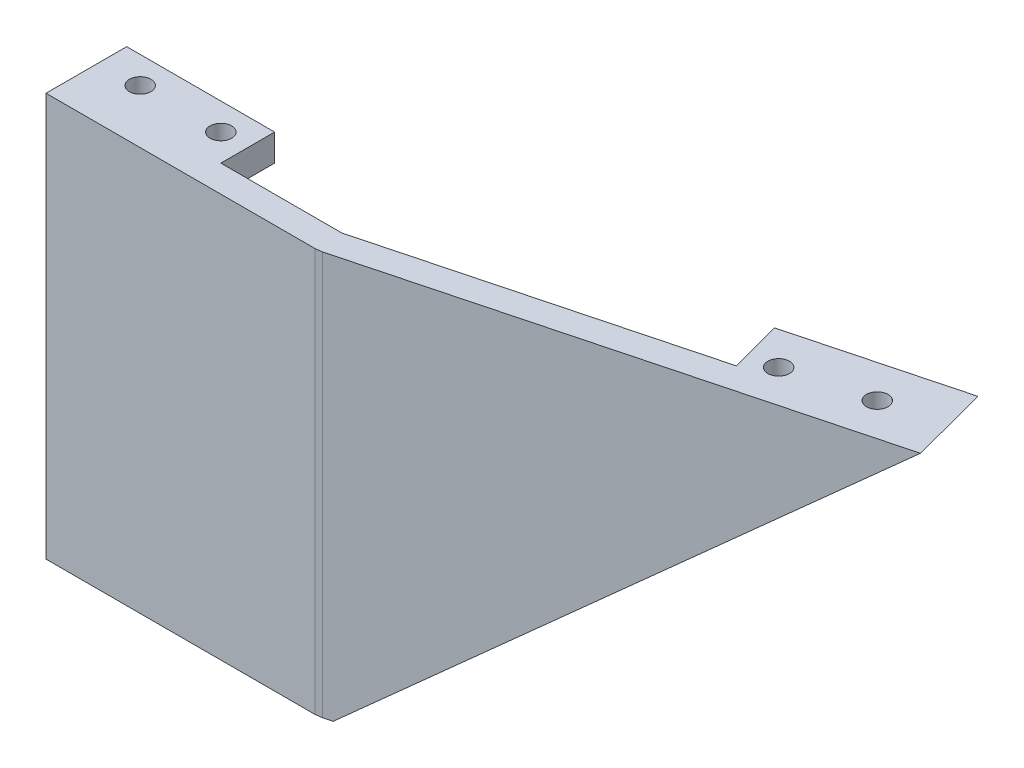
SolidWorks part; units mm, degrees
ref_plane "前视基准面" through (0, 0, 0) normal (0, 0, 1) x (1, 0, 0)
ref_plane "上视基准面" through (0, 0, 0) normal (0, 1, 0) x (1, 0, 0)
ref_plane "右视基准面" through (0, 0, 0) normal (1, 0, 0) x (0, 0, -1)
sketch "草图1" plane through (0, 0, 0) normal (0, 0, 1) x (1, 0, 0)
  line L1 (-25, 75) -> (25, 75)
  line L2 (-25, 75) -> (-25, -75)
  line L3 (-25, -75) -> (25, -75)
  line L4 (25, 75) -> (25, -75)
  line L5 (0, -75) -> (0, 75) construction
  line L6 (-25, 0) -> (25, 0) construction
  point P0 (0, 0)
  dimension "D1" = 50
  dimension "D2" = 150
extrude "凸台-拉伸1" add sketch "草图1" along normal blind 10
sketch "草图2" plane through (0, 75, 0) normal (0, 1, 0) x (1, 0, 0)
  line L0 (-13, -10) -> (25, 0)
  line L2 (25, -10) -> (-25, -10) construction
  line L3 (-25, -10) -> (-25, 0) construction
  dimension "D1" = 12
ref_plane "基准面1" through (25, 75, 0) normal (0.9671, 0, -0.2545) x (-0.2545, 0, -0.9671)
sketch "草图3" plane through (25, 75, 0) normal (0.9671, 0, -0.2545) x (-0.2545, 0, -0.9671)
  line L1 (0, 0) -> (-10, 0)
  line L2 (0, 0) -> (0, -150)
  line L3 (0, -150) -> (-10, -150)
  line L4 (-10, 0) -> (-10, -150)
  dimension "D1" = 10
extrude "凸台-拉伸2" add sketch "草图3" along normal blind 280 separate body
sketch "草图4" plane through (25, 0, 0) normal (1, 0, 0) x (0, 0, -1)
  line L1 (-10, 75) -> (0, 75)
  line L2 (-10, 75) -> (-10, -75)
  line L3 (-10, -75) -> (0, -75)
  line L4 (0, 75) -> (0, -75)
sketch "草图5" plane through (23.3808, 0, -6.1528) normal (-0.9671, 0, 0.2545) x (0.2545, 0, 0.9671)
  line L1 (6.3623, 75) -> (16.3623, 75)
  line L2 (6.3623, 75) -> (6.3623, -75)
  line L3 (6.3623, -75) -> (16.3623, -75)
  line L4 (16.3623, 75) -> (16.3623, -75)
loft "放样8" add profiles "草图4", "草图5"
sketch "草图6" plane through (0, 75, 0) normal (0, 1, 0) x (1, 0, 0)
  line L0 (25, 0) -> (295.7809, 71.2581)
  line L1 (-25, 0) -> (25, 0)
  line L2 (-25, 0) -> (-25, 20)
  line L3 (-25, 20) -> (22.4125, 20)
  line L6 (295.7809, 71.2581) -> (290.691, 90.5996)
  line L7 (22.4125, 20) -> (290.691, 90.5996)
  dimension "D1" = 20
  dimension "D2" = 20
extrude "凸台-拉伸3" add sketch "草图6" against normal blind 10
sketch "草图7" plane through (1.6192, 0, 6.1528) normal (-0.2545, 0, -0.9671) x (-0.9671, 0, 0.2545)
  line L0 (-194.1769, 65) -> (-24.1769, -77.6469)
  line L1 (-304.1769, 65) -> (-26.7644, 65) construction
  line L2 (-24.1769, -75) -> (-24.1769, 65) construction
  line L3 (-24.1769, -77.6469) -> (26.7218, -75)
  line L4 (26.7218, -75) -> (44.2616, -115.4721)
  line L5 (44.2616, -115.4721) -> (-316.3235, -105.2869)
  line L6 (-316.3235, -105.2869) -> (-321.0351, 79.2961)
  line L7 (-321.0351, 79.2961) -> (-302.3028, 102.6817)
  line L8 (-302.3028, 102.6817) -> (-235.3154, 89.4169)
  line L9 (-194.1769, 65) -> (-227.1481, 92.6661)
  line L10 (-227.1481, 92.6661) -> (-235.3154, 89.4169)
  dimension "D1" = 40
  dimension "D2" = 110
extrude "切除-拉伸1" cut sketch "草图7" against normal mid plane 100
sketch "草图8" plane through (-25, 0, 0) normal (-1, 0, 0) x (0, 0, 1)
  line L6 (0, 65) -> (0, -75)
  line L7 (0, -75) -> (10, -75)
  line L8 (10, -75) -> (10, 75)
  line L9 (10, 75) -> (-20, 75)
  line L10 (-20, 75) -> (-20, 65)
  line L11 (-20, 65) -> (0, 65)
  line L12 (0, 65) -> (0, -75)
  line L14 (10, -75) -> (10, 75)
  line L15 (10, 75) -> (-20, 75)
  line L16 (-20, 75) -> (-20, 65)
  line L17 (-20, 65) -> (0, 65)
  line L18 (0, -75) -> (10, -75)
  dimension "D1" = 0
extrude "凸台-拉伸4" add sketch "草图8" along normal blind 50
sketch "草图9" plane through (0, 65, 0) normal (0, -1, 0) x (1, 0, 0)
  line L0 (-75, -20) -> (-75, 0) construction
  line L1 (22.4125, -20) -> (-75, -20) construction
  line L2 (189.4027, -43.2639) -> (184.3128, -62.6054) construction
  line L3 (184.3128, -62.6054) -> (22.4125, -20) construction
  circle A0 centre (-60, -10) radius 4
  circle A1 centre (-30, -10) radius 4
  circle A2 centre (178.4595, -45.5543) radius 4
  circle A3 centre (149.4472, -37.9195) radius 4
  dimension "D1" = 8
  dimension "D6" = 10
  dimension "D8" = 15
  dimension "D2" = 15
  dimension "D3" = 10
  dimension "D4" = 30
  dimension "D5" = 30
  dimension "D7" = 15
extrude "切除-拉伸2" cut sketch "草图9" against normal blind 30
sketch "草图10" plane through (0, 75, 0) normal (0, 1, 0) x (1, 0, 0)
  line L1 (22.4125, 20) -> (-75, 20) construction
  line L6 (141.0489, 30.5392) -> (135.9591, 49.8807)
  line L7 (195.838, 65.6383) -> (22.4125, 20) construction
  line L8 (135.9591, 49.8807) -> (22.4125, 20)
  line L9 (22.4125, 20) -> (-20, 20)
  line L10 (-20, 20) -> (-20, 0)
  line L11 (-20, 0) -> (25, 0)
  line L12 (25, 0) -> (141.0489, 30.5392)
  dimension "D1" = 20
  dimension "D2" = 45
  dimension "D3" = 20
  dimension "D4" = 120
extrude "切除-拉伸4" cut sketch "草图10" against normal blind 10
